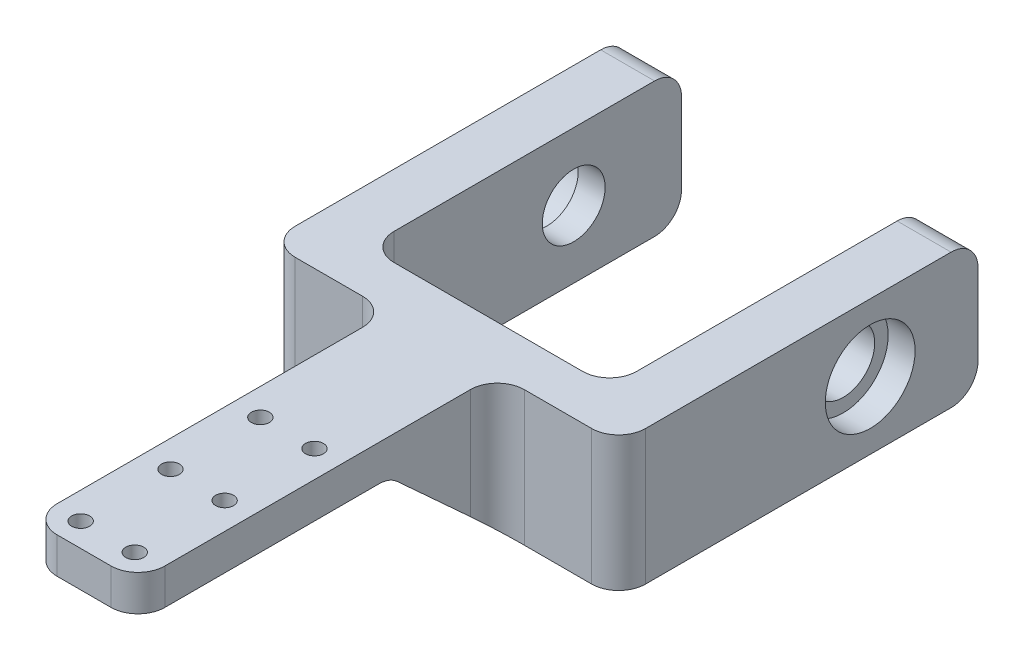
SolidWorks part; units mm, degrees
ref_plane "Front Plane" through (0, 0, 0) normal (0, 0, 1) x (1, 0, 0)
ref_plane "Top Plane" through (0, 0, 0) normal (0, 1, 0) x (1, 0, 0)
ref_plane "Right Plane" through (0, 0, 0) normal (1, 0, 0) x (0, 0, -1)
sketch "Sketch2" plane through (0, 0, 0) normal (0, 1, 0) x (1, 0, 0)
  line L0 (0, -736.4003) -> (0, 36083.6128) construction
  line L1 (-736.4003, 0) -> (36083.6128, 0) construction
  line L2 (-6, -40) -> (6, -40)
  line L3 (6, -40) -> (6, 0)
  line L4 (6, 0) -> (19.5, 0)
  line L5 (19.5, 0) -> (19.5, 40)
  line L6 (19.5, 40) -> (13.5, 40)
  line L7 (13.5, 40) -> (13.5, 5)
  line L8 (13.5, 5) -> (-13.5, 5)
  line L9 (-6, -40) -> (-6, 0)
  line L10 (-6, 0) -> (-19.5, 0)
  line L11 (-13.5, 40) -> (-13.5, 5)
  line L12 (-19.5, 0) -> (-19.5, 40)
  line L13 (-19.5, 40) -> (-13.5, 40)
  point P14 (0, -40)
  point P17 (0, 5)
  dimension "D1" = 40
  dimension "D2" = 45
  dimension "D3" = 80
  dimension "D4" = 6
  dimension "D5" = 6
  dimension "D6" = 40
  dimension "D7" = 27
extrude "Boss-Extrude1" add sketch "Sketch2" along normal blind 15
sketch "Sketch3" plane through (19.5, 0, 0) normal (1, 0, 0) x (0, 0, -1)
  line L6 (-960, 7.5) -> (49040, 7.5) construction
  line L7 (40, 15) -> (40, 0) construction
  circle A0 centre (28, 7.5) radius 5
  point P5 (40, 7.5)
  dimension "D1" = 10
  dimension "D2" = 12
extrude "Cut-Extrude1" cut sketch "Sketch3" against normal blind 3
sketch "Sketch4" plane through (-19.5, 0, 0) normal (-1, 0, 0) x (0, 0, 1)
  line L0 (-1040, 7.5) -> (48960, 7.5) construction
  line L1 (-40, 15) -> (-40, 0) construction
  circle A0 centre (-28, 7.5) radius 5
  point P5 (-40, 7.5)
  dimension "D1" = 12
  dimension "D2" = 10
extrude "Cut-Extrude2" cut sketch "Sketch4" against normal blind 3
sketch "Sketch5" plane through (16.5, 0, 0) normal (1, 0, 0) x (0, 0, -1)
  line L0 (28, 12.5) -> (28, 2.5) construction
  line L1 (23, 7.5) -> (33, 7.5) construction
  circle A0 centre (28, 7.5) radius 5 construction
  circle A1 centre (28, 7.5) radius 5 construction
  circle A2 centre (28, 7.5) radius 3.5
  dimension "D1" = 7
extrude "Cut-Extrude3" cut sketch "Sketch5" against normal blind 64
sketch "Sketch6" plane through (-6, 0, 0) normal (-1, 0, 0) x (0, 0, 1)
  line L0 (40, 15) -> (40, 11)
  line L1 (40, 15) -> (40, 0) construction
  line L2 (40, 11) -> (12, 11)
  line L3 (12, 11) -> (0, 0)
  line L4 (0, 0) -> (40, 0)
  line L5 (40, 0) -> (40, 11)
  line L6 (0, 15) -> (40, 15) construction
  point P11 (0, 0)
  line M3 (0, 0) -> (40, 0)
  line M4 (40, 0) -> (40, 15)
  dimension "D1" = 4
  dimension "D2" = 28
extrude "Cut-Extrude4" cut sketch "Sketch6" against normal blind 15 contours L2 L3 M3 M4
fillet "Fillet2" radius 3 4 edges at (-16.5, 0, -40) (-16.5, 15, -40) (16.5, 0, -40) (16.5, 15, -40)
fillet "Fillet3" radius 3 4 edges at (19.5, 7.5, 0) (13.5, 7.5, -5) (-13.5, 7.5, -5) (-19.5, 7.5, 0)
fillet "Fillet5" radius 3 3 edges at (0, 11, 12) (-6, 7.5, 0) (6, 7.5, 0)
fillet "Fillet6" radius 3 2 edges at (6, 13, 40) (-6, 13, 40)
sketch "Sketch7" plane through (0, 11, 0) normal (0, -1, 0) x (1, 0, 0)
  line L0 (0, 40) -> (0, 13.167) construction
  line L1 (3, 40) -> (-3, 40) construction
  line L2 (-6, 13.167) -> (6, 13.167) construction
  circle A0 centre (-3.0105, 37.3655) radius 1
  circle A1 centre (-3.0105, 27.3655) radius 1
  circle A2 centre (-3.0105, 17.3655) radius 1
  circle A3 centre (3.0105, 17.3655) radius 1
  circle A4 centre (3.0105, 27.3655) radius 1
  circle A5 centre (3.0105, 37.3655) radius 1
  dimension "D1" = 2
  dimension "D2" = 3
extrude "Cut-Extrude5" cut sketch "Sketch7" against normal blind 4
